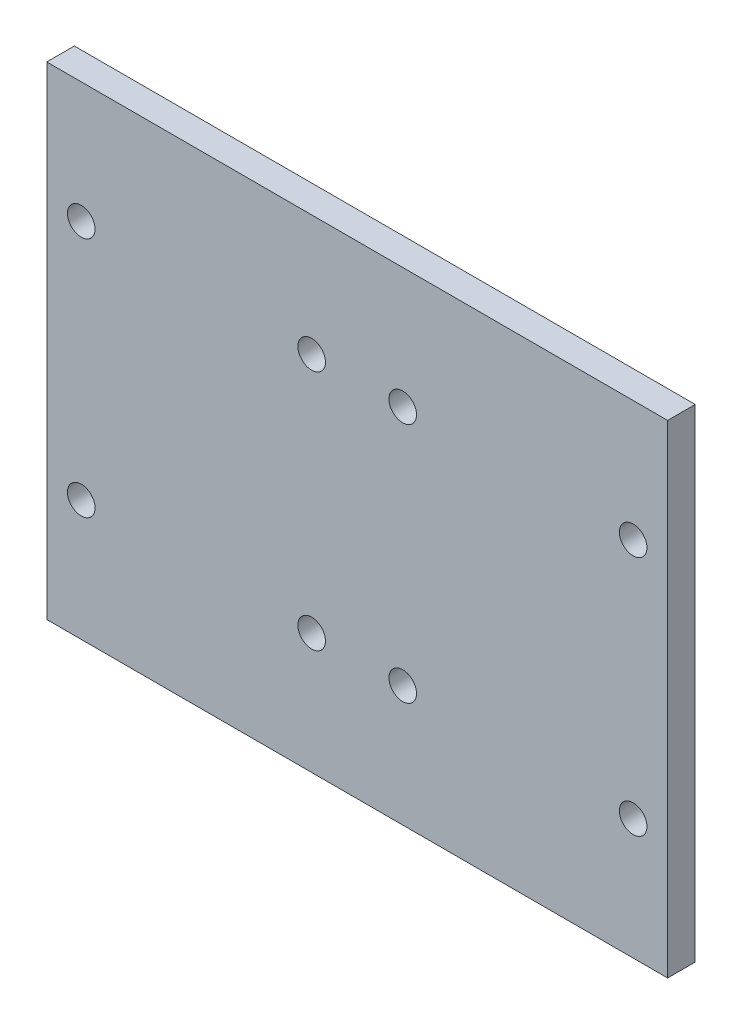
SolidWorks part; units mm, degrees
ref_plane "Front Plane" through (0, 0, 0) normal (0, 0, 1) x (1, 0, 0)
ref_plane "Top Plane" through (0, 0, 0) normal (0, 1, 0) x (1, 0, 0)
ref_plane "Right Plane" through (0, 0, 0) normal (1, 0, 0) x (0, 0, -1)
sketch "Sketch1" plane through (0, 0, 0) normal (0, 0, 1) x (1, 0, 0)
  line L4 (-67.538, 0) -> (61.6563, 0) construction
  line L5 (0, 31.0047) -> (0, -34.6671) construction
  line L6 (-45, 35) -> (-45, -35)
  line L7 (-45, -35) -> (45, -35)
  line L8 (45, -35) -> (45, 35)
  line L9 (45, 35) -> (-45, 35)
  circle A0 centre (-6.6, 17.5) radius 2
  circle A2 centre (6.6, 17.5) radius 2
  circle A3 centre (-6.6, -17.5) radius 2
  circle A4 centre (-40, 17.5) radius 2
  circle A5 centre (-40, -17.5) radius 2
  circle A6 centre (40, 17.5) radius 2
  circle A8 centre (6.6, -17.5) radius 2
  circle A9 centre (40, -17.5) radius 2
  dimension "D1" = 4
  dimension "D2" = 4
  dimension "D3" = 4
  dimension "D4" = 4
  dimension "D5" = 4
  dimension "D6" = 4
  dimension "D7" = 4
  dimension "D10" = 4
  dimension "D8" = 17.5
  dimension "D9" = 33.4
  dimension "D11" = 17.5
  dimension "D12" = 33.4
  dimension "D13" = 33.4
  dimension "D14" = 6.6
  dimension "D15" = 6.6
  dimension "D16" = 33.4
  dimension "D17" = 35
  dimension "D18" = 70
  dimension "D19" = 90
  dimension "D20" = 45
  dimension "D21" = 35
extrude "Boss-Extrude1" add sketch "Sketch1" along normal blind 4
